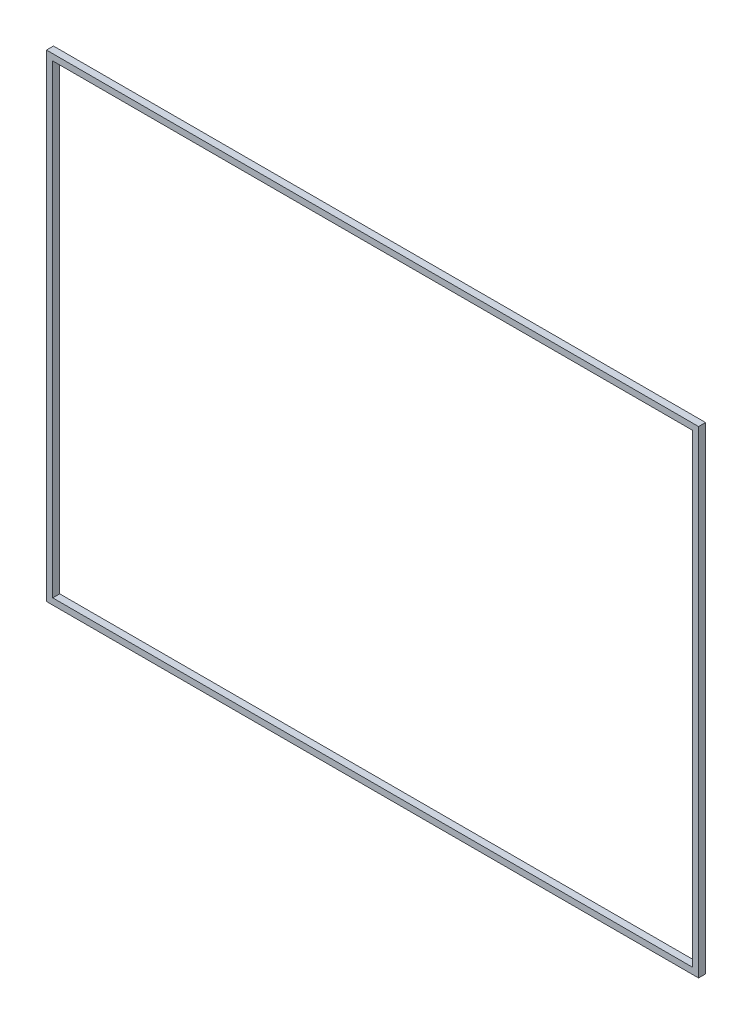
SolidWorks part; units mm, degrees
ref_plane "Front Plane" through (0, 0, 0) normal (0, 0, 1) x (1, 0, 0)
ref_plane "Top Plane" through (0, 0, 0) normal (0, 1, 0) x (1, 0, 0)
ref_plane "Right Plane" through (0, 0, 0) normal (1, 0, 0) x (0, 0, -1)
other "Configuration Table"
sketch "Sketch1" plane through (0, 0, 0) normal (0, 0, 1) x (1, 0, 0)
  line L0 (-93.4, -68.4) -> (93.4, -68.4)
  line L1 (93.4, -68.4) -> (93.4, 68.4)
  line L2 (93.4, 68.4) -> (-93.4, 68.4)
  line L3 (-93.4, 68.4) -> (-93.4, -68.4)
  line L4 (-91.6, -66.6) -> (91.6, -66.6)
  line L5 (91.6, -66.6) -> (91.6, 66.6)
  line L6 (91.6, 66.6) -> (-91.6, 66.6)
  line L7 (-91.6, 66.6) -> (-91.6, -66.6)
extrude "Gasket" add sketch "Sketch1" along normal blind 2 from offset 42.5
equation "\"Jar_OD\"= 90  'ASSUMED - Part G fallback - jar outer diameter"
equation "\"Jar_H\"= 120  'ASSUMED - Part G fallback - jar height"
equation "\"Pump_L\"= 45  'ASSUMED - Part G fallback"
equation "\"Pump_W\"= 24  'ASSUMED - Part G fallback"
equation "\"Pump_H\"= 33  'ASSUMED - Part G fallback"
equation "\"Pump_Outlet_OD\"= 7.5  'ASSUMED - Part G fallback"
equation "\"Tube_OD\"= 8  'ASSUMED - Part G fallback"
equation "\"Tube_ID\"= 6  'ASSUMED - Part G fallback"
equation "\"TDS_Body_Dia\"= 12  'ASSUMED - Part G fallback"
equation "\"TDS_Wet_Len\"= 45  'ASSUMED - Part G fallback - length in water"
equation "\"DS_Tube_Dia\"= 6  'ASSUMED - Part G fallback"
equation "\"DS_Tube_Len\"= 50  'ASSUMED - Part G fallback"
equation "\"ORP_Body_Dia\"= 12  'ASSUMED - Part G fallback"
equation "\"ORP_Body_Len\"= 150  'ASSUMED - Part G fallback"
equation "\"ORP_Cap_Dia\"= 16  'ASSUMED - Part G fallback"
equation "\"Turb_W\"= 33  'ASSUMED - Part G fallback - head width"
equation "\"Turb_D\"= 28  'ASSUMED - Part G fallback - head depth"
equation "\"Turb_H\"= 30  'ASSUMED - Part G fallback - head height"
equation "\"Turb_Slot_W\"= 10  'ASSUMED - Part G fallback - slot width"
equation "\"Flow_L\"= 62  'ASSUMED - Part G fallback YF-S201"
equation "\"Flow_W\"= 36  'ASSUMED - Part G fallback"
equation "\"Flow_H\"= 35  'ASSUMED - Part G fallback"
equation "\"Thread_G12_OD\"= 20.955  'ASSUMED - Part G fallback thread G1/2 (major diameter)"
equation "\"Valve_L\"= 75  'ASSUMED - Part G fallback"
equation "\"Valve_W\"= 45  'ASSUMED - Part G fallback"
equation "\"Valve_H\"= 60  'ASSUMED - Part G fallback"
equation "\"Tee_L\"= 40  'ASSUMED - Part G fallback - overall length"
equation "\"Tee_Branch_L\"= 25  'ASSUMED - Part G fallback"
equation "\"Tee_OD\"= 12  'ASSUMED - Part G fallback"
equation "\"LED_Board_L\"= 20  'ASSUMED - Part G fallback"
equation "\"LED_Board_W\"= 20  'ASSUMED - Part G fallback - LED at centre"
equation "\"GUVA_L\"= 20  'ASSUMED - Part G fallback"
equation "\"GUVA_W\"= 12  'ASSUMED - Part G fallback - sensor at centre"
equation "\"Reed_L\"= 27  'ASSUMED - Part G fallback MC-38 half"
equation "\"Reed_W\"= 14  'ASSUMED - Part G fallback"
equation "\"Reed_H\"= 8  'ASSUMED - Part G fallback"
equation "\"ESP_L\"= 51  'ASSUMED - Part G fallback"
equation "\"ESP_W\"= 28  'ASSUMED - Part G fallback"
equation "\"TFT_L\"= 58  'ASSUMED - Part G fallback - board"
equation "\"TFT_W\"= 35  'ASSUMED - Part G fallback - board"
equation "\"TFT_Win_L\"= 35  'ASSUMED - Part G fallback - visible window"
equation "\"TFT_Win_W\"= 28  'ASSUMED - Part G fallback - visible window"
equation "\"Relay_L\"= 50  'ASSUMED - Part G fallback"
equation "\"Relay_W\"= 26  'ASSUMED - Part G fallback"
equation "\"Relay_H\"= 19  'ASSUMED - Part G fallback"
equation "\"Mosfet_L\"= 34  'ASSUMED - Part G fallback"
equation "\"Mosfet_W\"= 17  'ASSUMED - Part G fallback"
equation "\"Mosfet_H\"= 12  'ASSUMED - Part G fallback"
equation "\"TDS_Board_L\"= 42  'ASSUMED - Part G fallback"
equation "\"TDS_Board_W\"= 32  'ASSUMED - Part G fallback"
equation "\"Turb_Board_L\"= 38  'ASSUMED - Part G fallback"
equation "\"Turb_Board_W\"= 28  'ASSUMED - Part G fallback"
equation "\"BNC_Thread_Dia\"= 9.5  'ASSUMED - Part G fallback"
equation "\"Plate_L\"= 420  'ASSUMED - Part G fallback"
equation "\"Plate_W\"= 297  'ASSUMED - Part G fallback"
equation "\"Plate_T\"= 6  'ASSUMED - Part G fallback"
equation "\"Booster_L\"= 150  'ASSUMED - Part G fallback - booster pump"
equation "\"Booster_W\"= 95  'ASSUMED - Part G fallback"
equation "\"Booster_H\"= 100  'ASSUMED - Part G fallback"
equation "\"PTube_OD\"= 6.35  'ASSUMED - Part G fallback - product tube 1/4 inch"
equation "\"Qz_Out\"= 12  'ASSUMED - Part G fallback - quartz channel outside square"
equation "\"Qz_Path\"= 10  'ASSUMED - Part G fallback - quartz channel inside light path"
equation "\"Qz_L\"= 40  'ASSUMED - Part G fallback - quartz channel length"
equation "\"LED860_Dia\"= 5  'ASSUMED - Part G fallback - 860 nm LED"
equation "\"BPW_L\"= 5.4  'ASSUMED - Part G fallback - BPW34"
equation "\"BPW_W\"= 4.3  'ASSUMED - Part G fallback - BPW34"
equation "\"Cart_Dia\"= 50  'ASSUMED - Part G fallback - sediment and pre-carbon cartridges"
equation "\"Cart_L\"= 255  'ASSUMED - Part G fallback"
equation "\"UF_Dia\"= 50  'ASSUMED - Part G fallback - UF cartridge"
equation "\"UF_L\"= 260  'ASSUMED - Part G fallback"
equation "\"RO_Dia\"= 62  'ASSUMED - Part G fallback - RO membrane housing"
equation "\"RO_L\"= 300  'ASSUMED - Part G fallback"
equation "\"UVC_Dia\"= 40  'ASSUMED - Part G fallback - UV-C chamber"
equation "\"UVC_L\"= 300  'ASSUMED - Part G fallback"
equation "\"Tank_W\"= 260  'ASSUMED - Part G fallback - storage tank"
equation "\"Tank_D\"= 160  'ASSUMED - Part G fallback"
equation "\"Tank_H\"= 300  'ASSUMED - Part G fallback"
equation "\"Cab_W\"= 400  'ASSUMED - Part G fallback - purifier cabinet"
equation "\"Cab_D\"= 270  'ASSUMED - Part G fallback"
equation "\"Cab_H\"= 560  'ASSUMED - Part G fallback"
equation "\"ORP_Board_L\"= 40  'ASSUMED - Part G fallback - ORP buffer board"
equation "\"ORP_Board_W\"= 30  'ASSUMED - Part G fallback"
equation "\"Opt_Board_L\"= 50  'ASSUMED - Part G fallback - optical front-end board"
equation "\"Opt_Board_W\"= 40  'ASSUMED - Part G fallback"
equation "\"Buck_L\"= 43  'ASSUMED - Part G fallback - 12 V to 5 V buck module"
equation "\"Buck_W\"= 21  'ASSUMED - Part G fallback"
equation "\"Buck_H\"= 14  'ASSUMED - Part G fallback"
equation "\"BB_L\"= 165  'ASSUMED - Part G fallback - breadboard (As_Built_R3 only)"
equation "\"BB_W\"= 55  'ASSUMED - Part G fallback"
equation "\"BB_H\"= 10  'ASSUMED - Part G fallback"
equation "\"Cuv_W\"= 12.5  'ASSUMED - old R3 cuvette (station suppressed in SS4)"
equation "\"Cuv_D\"= 12.5  'ASSUMED - old R3 cuvette (station suppressed in SS4)"
equation "\"Cuv_H\"= 45  'ASSUMED - old R3 cuvette (station suppressed in SS4)"
equation "\"Probe_Clr\"= 0.3  'DESIGN VALUE - Part C rule 3 - printed probe hole = diameter + 0.3"
equation "\"Label_H\"= 0.6  'DESIGN VALUE - Part D - raised label height"
